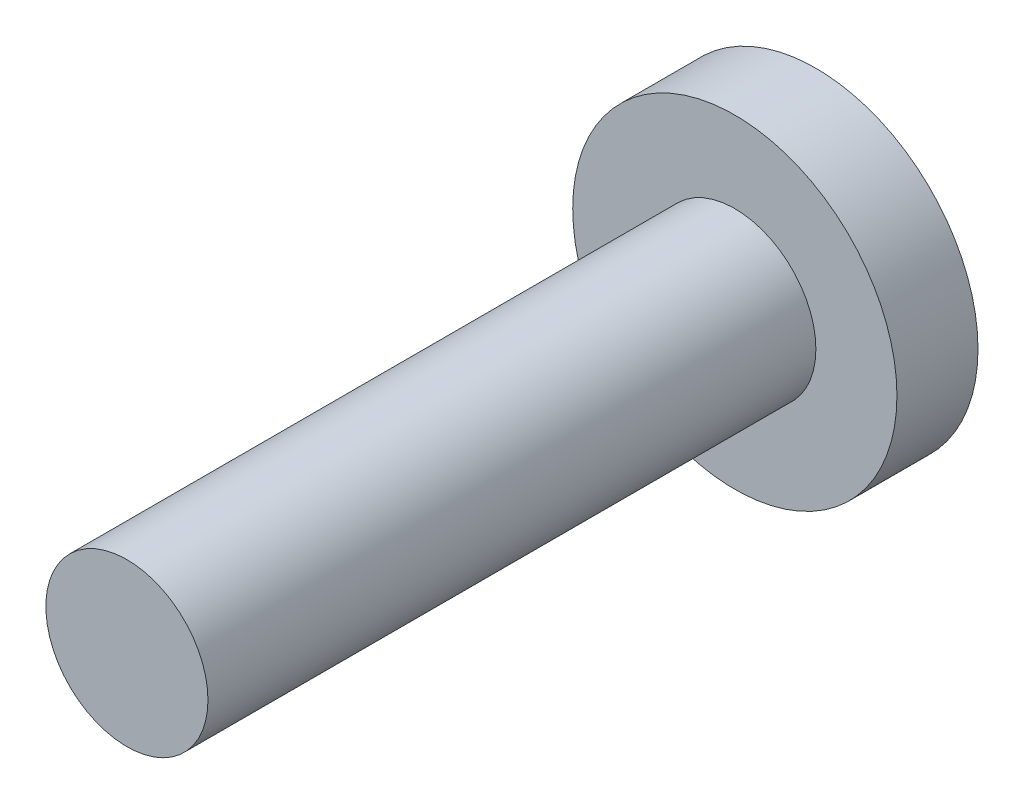
SolidWorks part; units mm, degrees
ref_plane "Front Plane" through (0, 0, 0) normal (0, 0, 1) x (1, 0, 0)
ref_plane "Top Plane" through (0, 0, 0) normal (0, 1, 0) x (1, 0, 0)
ref_plane "Right Plane" through (0, 0, 0) normal (1, 0, 0) x (0, 0, -1)
sketch "Sketch1" plane through (0, 0, 0) normal (0, 0, 1) x (1, 0, 0)
  circle A0 centre (0, 0) radius 2
extrude "Reference_Head" add sketch "Sketch1" along normal blind 1 from offset 1
sketch "Sketch2" plane through (0, 0, 0) normal (0, 0, 1) x (1, 0, 0)
  circle A0 centre (0, 0) radius 1
extrude "Reference_Shank" add sketch "Sketch2" along normal blind 7.5
